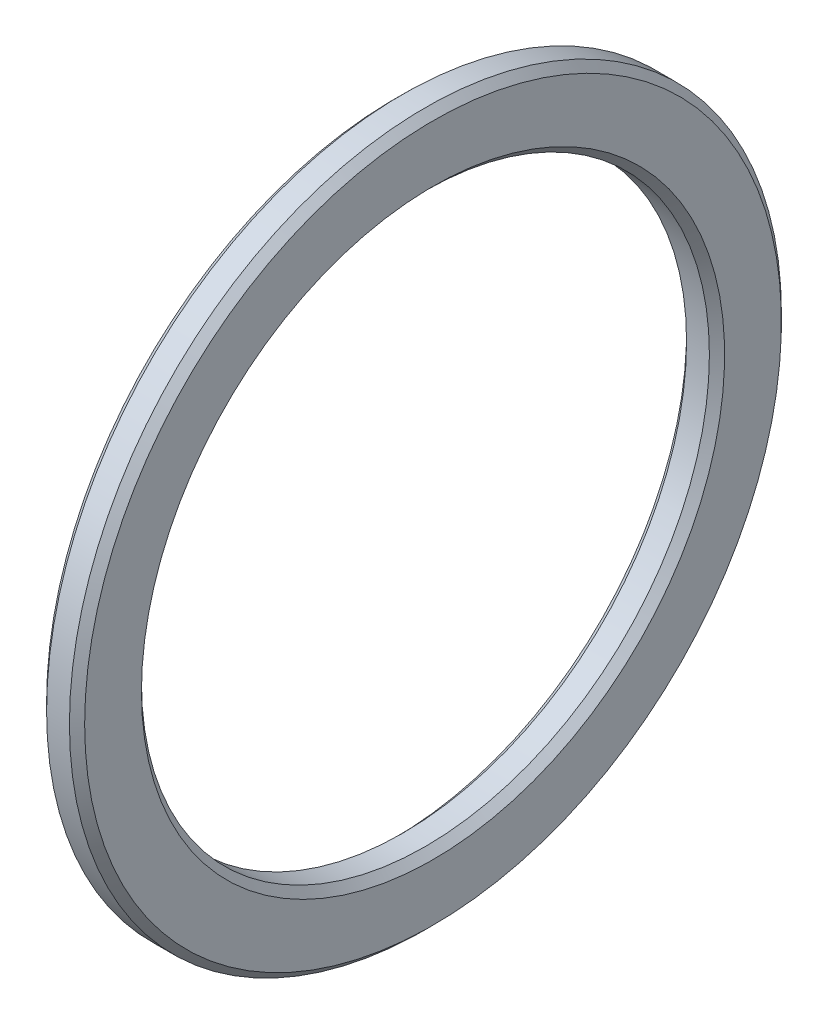
SolidWorks part; units mm, degrees
ref_plane "Plan de face" through (0, 0, 0) normal (0, 0, 1) x (1, 0, 0)
ref_plane "Plan de dessus" through (0, 0, 0) normal (0, 1, 0) x (1, 0, 0)
ref_plane "Plan de droite" through (0, 0, 0) normal (1, 0, 0) x (0, 0, -1)
sketch "Esquisse1" plane through (0, 0, 0) normal (0, 0, 1) x (1, 0, 0)
  line L0 (-10.6551, 0) -> (91.9494, 0) construction
  line L1 (0, 22.88) -> (0.5, 23.38)
  line L2 (0.5, 23.38) -> (2, 23.38)
  line L3 (0, 22.88) -> (0, 19.15)
  line L4 (0.5, 18.65) -> (2, 18.65)
  line L5 (2.5, 22.88) -> (2.5, 19.15)
  line L6 (0, 19.15) -> (0.5, 18.65)
  line L7 (2, 18.65) -> (2.5, 19.15)
  line L8 (2, 23.38) -> (2.5, 22.88)
  point P3 (0, 23.38)
  point P4 (2.5, 18.65)
  point P5 (0, 18.65)
  point P6 (2.5, 23.38)
  dimension "D1" = 2.5
  dimension "D2" = 37.3
  dimension "D3" = 46.76
  dimension "D6" = 0.5
  dimension "D7" = 0.5
  dimension "D8" = 0.5
  dimension "D9" = 0.5
revolve "Révolution1" add sketch "Esquisse1" angle 360 about L0
